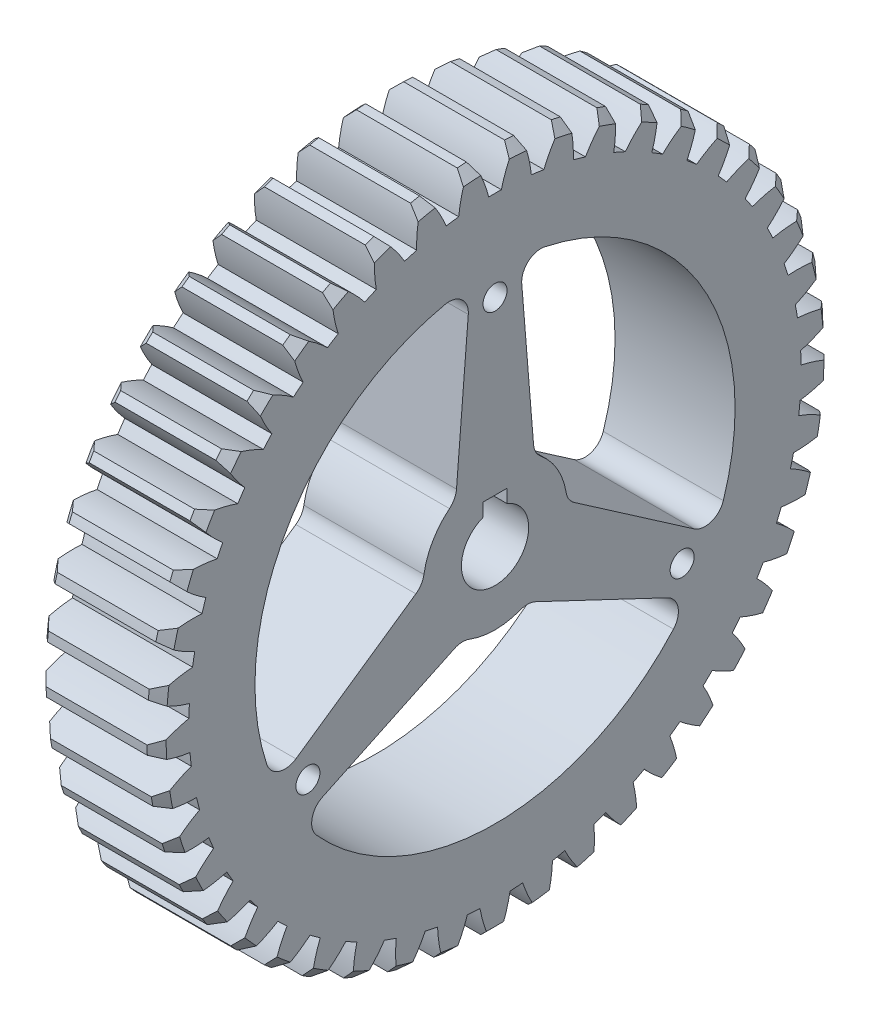
SolidWorks part; units mm, degrees
ref_plane "Plane1" through (0, 0, 0) normal (0, 0, 1) x (1, 0, 0)
ref_plane "Plane2" through (0, 0, 0) normal (0, 1, 0) x (1, 0, 0)
ref_plane "Plane3" through (0, 0, 0) normal (1, 0, 0) x (0, 0, -1)
sketch "HoldingSke" plane through (0, 0, 0) normal (0, 1, 0) x (1, 0, 0)
  line L0 (0, 0) -> (0.2357, -0.2357)
  line L1 (-15, 0) -> (100, 0) construction
  line L2 (0, 0) -> (-2.1039, 2.3779)
  line L3 (0, 0) -> (-11.863, 4.5341)
  line L4 (0, 0) -> (6.1066, 6.1066)
  line L5 (0, 0) -> (-46.8476, -17.4728)
  line L6 (0, 0) -> (-24.8689, -16.7791)
  line L7 (-2.1039, 2.3779) -> (8.6586, 51.2059)
  line L8 (-76.2, 54.61) -> (-73.9, 54.61)
  line L9 (-71.009, 38.7566) -> (-53.1078, 45.2721)
  line L10 (-76.2, 71.12) -> (104.1128, 71.12)
  line L11 (0, 0) -> (-30, 0)
  line L12 (-76.2, 101.6) -> (-76.093, 101.6)
  line L13 (24.9733, 27.94) -> (52.9518, 28.4284)
  line L14 (24.9733, 27.94) -> (24.9743, 27.94)
  line L15 (24.9733, 27.94) -> (100.4006, 29.5858)
  line L16 (-63.627, -3) -> (-12.827, -3)
  circle A0 centre (0, 0) radius 7
  circle A1 centre (0, 0) radius 37.5
  circle A2 centre (0, 0) radius 37.5
  circle A3 centre (0, 0) radius 7
  dimension "MHD" = 75
  dimension "Hub_dia" = 75
  dimension "Bore" = 14
  dimension "MBD" = 14
  dimension "Num_teeth" = 45
  dimension "Pitch" = 0.3333
  dimension "Overall_len" = 50
  dimension "Show_teeth" = 45
  dimension "Thickness" = 30
  dimension "OAL" = 50.0001
  dimension "T_dim" = 2.3
  dimension "Ap" = 20
  dimension "H" = 19.05
  dimension "Pitch_radius" = 180.3128
  dimension "Width" = 30
  dimension "Backlash" = 0.107
  dimension "Addendum_fac" = 1
  dimension "Dedendum_fac" = 1.25
  dimension "Clearance_fac" = 0.25
  dimension "Dedendum_add" = 0.001
  dimension "Module" = 3
sketch "BasProSke" plane through (0, 0, 0) normal (0, 1, 0) x (1, 0, 0)
  line L0 (-10, 0) -> (60, 0) construction
  line L1 (0, 0) -> (0, 70.5)
  line L2 (0, 0) -> (25, 0)
  line L3 (25, 0) -> (25, 70.5)
  line L4 (25, 70.5) -> (0, 70.5)
  dimension "Thickness" = 25
  dimension "Diameter" = 141
revolve "Base-Revolve" add sketch "BasProSke" angle 360 about L0
chamfer "倒角1" distance 2 angle 45 2 edges at (25, 0, 70.5) (0, 0, 70.5)
sketch "TooCutSke" plane through (0, 0, 0) normal (1, 0, 0) x (0, 0, -1)
  line L1 (0, 0) -> (0, 107) construction
  line L2 (0, 0) -> (-2.5429, 67.4521) construction
  line L3 (0, 0) -> (-9.4123, 134.6016) construction
  line L4 (-2.5429, 67.4521) -> (-4.7061, 67.3008) construction
  arc A0 (1.3167, 63.7354) -> (-1.3167, 63.7354) centre (0, 0) ccw
  arc A1 (3.9813, 70.4129) -> (-3.9813, 70.4129) centre (0, 0) ccw
  circle A2 centre (0, 0) radius 67.5 construction
  circle A3 centre (0, 0) radius 63.4293 construction
  arc A4 (-1.3167, 63.7354) -> (-3.9813, 70.4129) centre (-27.5029, 57.1564) ccw
  arc A5 (3.9813, 70.4129) -> (1.3167, 63.7354) centre (27.5029, 57.1564) ccw
  dimension "Root_dia" = 127.498
  dimension "Overcut_dia" = 141.0508
  dimension "Pitch_dia" = 135
  dimension "Base_dia" = 126.8585
  dimension "Flank_rad" = 27
  dimension "Half_ang" = 4
  dimension "Half_CT" = 2.1685
extrude "ToothCut" cut sketch "TooCutSke" along normal through all
fillet "Breaks" [suppressed] radius 0.06
fillet "RootFillets" [suppressed] radius 0.751
pattern_circular "TeethCuts" count 45 every 8 about axis through (-10, 0, 0) along (1, 0, 0) of "ToothCut", "RootFillets", "Breaks"
sketch "HubNeaOneSke" plane through (0, 0, 0) normal (-1, 0, 0) x (0, 0, 1)
  circle A0 centre (0, 0) radius 37.5
  dimension "Diameter" = 75
extrude "HubNearOne" [suppressed] add sketch "HubNeaOneSke" along normal blind 25.0001
sketch "HubNeaBotSke" plane through (0, 0, 0) normal (-1, 0, 0) x (0, 0, 1)
  circle A0 centre (0, 0) radius 37.5
  dimension "Diameter" = 75
extrude "HubNearBoth" [suppressed] add sketch "HubNeaBotSke" along normal blind 12.5
ref_plane "FarPln" through (25, 0, 0) normal (1, 0, 0) x (0, 0, -1)
sketch "HubFarSke" plane through (25, 0, 0) normal (1, 0, 0) x (0, 0, -1)
  circle A0 centre (0, 0) radius 37.5
  dimension "Diameter" = 75
extrude "HubFar" [suppressed] add sketch "HubFarSke" along normal blind 12.5
sketch "BorSke" plane through (0, 0, 0) normal (1, 0, 0) x (0, 0, -1)
  circle A0 centre (0, 0) radius 7
  dimension "Diameter" = 14
extrude "Bore" cut sketch "BorSke" along normal mid plane 100.0001
sketch "KeySke" plane through (0, 0, 0) normal (1, 0, 0) x (0, 0, -1)
  line L0 (-2.5, 0) -> (-2.5, 9.3)
  line L1 (-2.5, 9.3) -> (2.5, 9.3)
  line L2 (2.5, 9.3) -> (2.5, 0)
  line L3 (0, 0) -> (0, 34) construction
  line L4 (-2.5, 0) -> (2.5, 0)
  dimension "Offset" = 9.3
  dimension "Width" = 5
extrude "Keyway" cut sketch "KeySke" along normal mid plane 100.0001
pattern_circular "Keyway2" [suppressed] count 2 every 90 about axis through (-10, 0, 0) along (1, 0, 0)
sketch "草图1" plane through (0, 0, 0) normal (1, 0, 0) x (0, 0, -1)
  line L2 (0, 0) -> (-12.9904, 7.5) construction
  line L3 (-5.1571, 49.7333) -> (-8.1725, 12.5782)
  line L4 (0, 67.7355) -> (0, 0) construction
  line L5 (-45.6489, -20.4005) -> (-14.9793, 0.7885)
  line L6 (45.6489, -20.4005) -> (14.9793, 0.7885)
  line L7 (5.1571, 49.7333) -> (8.1725, 12.5782)
  line L8 (-40.4918, -29.3328) -> (-6.8068, -13.3667)
  line L9 (40.4918, -29.3328) -> (6.8068, -13.3667)
  arc A0 (-8.1725, 12.5782) -> (-14.9793, 0.7885) centre (0, 0) ccw
  arc A1 (-5.1571, 49.7333) -> (-45.6489, -20.4005) centre (0, 0) ccw
  circle A3 centre (-12.9904, 7.5) radius 7 construction
  circle A4 centre (-0.5157, 54.9733) radius 7 construction
  arc A5 (45.6489, -20.4005) -> (5.1571, 49.7333) centre (0, 0) ccw
  arc A6 (14.9793, 0.7885) -> (8.1725, 12.5782) centre (0, 0) ccw
  arc A7 (-40.4918, -29.3328) -> (40.4918, -29.3328) centre (0, 0) ccw
  arc A8 (-6.8068, -13.3667) -> (6.8068, -13.3667) centre (0, 0) ccw
  dimension "D2" = 14
  dimension "D3" = 100
  dimension "D4" = 3
  dimension "D5" = 30
  dimension "D6" = 14
  dimension "D1" = 60
extrude "切除-拉伸1" cut sketch "草图1" along normal through all
sketch "草图2" plane through (0, 0, 0) normal (1, 0, 0) x (0, 0, -1)
  circle A0 centre (0, 45) radius 2.5
  circle A4 centre (0, 0) radius 45 construction
  circle A5 centre (38.9711, -22.5) radius 2.5
  circle A6 centre (-38.9711, -22.5) radius 2.5
  dimension "D1" = 5
  dimension "D2" = 90
  dimension "D3" = 3
extrude "切除-拉伸2" cut sketch "草图2" along normal through all
sketch "草图3" plane through (0, 0, 0) normal (1, 0, 0) x (0, 0, -1)
  circle A0 centre (0, 30) radius 2
  circle A1 centre (25.9808, -15) radius 2
  circle A2 centre (-25.9808, -15) radius 2
  dimension "D1" = 4
  dimension "D3" = 3
extrude "切除-拉伸3" cut sketch "草图3" along normal blind 10
fillet "圆角1" radius 4 12 edges at (12.5, 12.5782, -8.1725) (12.5, 0.7885, -14.9793) (12.5, -13.3667, -6.8068) (12.5, -13.3667, 6.8068) (12.5, 0.7885, 14.9793) (12.5, 12.5782, 8.1725) (12.5, 49.7333, 5.1571) (12.5, 49.7333, -5.1571) (12.5, -20.4005, -45.6489) (12.5, -29.3328, -40.4918) (12.5, -29.3328, 40.4918) (12.5, -20.4005, 45.6489)
equation "' \"Module@HoldingSke\" = 6.35"
equation "' \"Num_teeth@HoldingSke\" = 12"
equation "' \"Ap@HoldingSke\" =  20"
equation "' \"Ap@HoldingSke\" = 20"
equation "' \"Width@HoldingSke\" = 0.5 * 25.4"
equation "' \"Hub_dia@HoldingSke\"= 1 * 25.4"
equation "' \"Hub_dia@HoldingSke\" = 1 * 25.4"
equation "' \"Overall_len@HoldingSke\" = 1.0 * 25.4"
equation "' \"Bore@HoldingSke\" = 0.75 * 25.4"
equation "' \"T_dim@HoldingSke\" = 0.1 * 25.4"
equation "' \"Width@KeySke\" = 0.25 * 25.4"
equation "' \"Show_teeth@HoldingSke\" = 13"
equation "' \"Backlash@HoldingSke\" = 0.009 * 25.4"
equation "' \"Addendum_fac@HoldingSke\" = 1.0"
equation "' \"Dedendum_fac@HoldingSke\" = 1.25"
equation "' \"Dedendum_add@HoldingSke\" = 0.00005 * 25.4"
equation "' \"Clearance_fac@HoldingSke\" = 0.25"
equation "\"Pitch@HoldingSke\" = 1 / \"Module@HoldingSke\""
equation "\"Overcut_dia@TooCutSke\" = (\"Num_teeth@HoldingSke\" + 2 * \"Addendum_fac@HoldingSke\") / \"Pitch@HoldingSke\" + 0.002 * 25.4"
equation "\"Pitch_dia@TooCutSke\" = \"Num_teeth@HoldingSke\" / \"Pitch@HoldingSke\""
equation "\"Base_dia@TooCutSke\" = \"Num_teeth@HoldingSke\" / \"Pitch@HoldingSke\" * cos((\"Ap@HoldingSke\"  * 3.14159265 / 180))"
equation "\"Root_dia@TooCutSke\" = (\"Num_teeth@HoldingSke\" + 2) / \"Pitch@HoldingSke\" - 2 * (\"Addendum_fac@HoldingSke\" + \"Dedendum_fac@HoldingSke\") / \"Pitch@HoldingSke\" - \"Dedendum_add@HoldingSke\" * 2"
equation "\"Half_ang@TooCutSke\" = 180 / \"Num_teeth@HoldingSke\""
equation "\"Half_CT@TooCutSke\" = \"Num_teeth@HoldingSke\" / \"Pitch@HoldingSke\" * sin((3.14159265 / 2 / \"Num_teeth@HoldingSke\")) / 2 - 7 * \"Backlash@HoldingSke\" / 4"
equation "\"Flank_rad@TooCutSke\" = \"Num_teeth@HoldingSke\" / \"Pitch@HoldingSke\" / 5"
equation "\"Radius@RootFillets\" = \"Clearance_fac@HoldingSke\" / \"Pitch@HoldingSke\" + \"Dedendum_add@HoldingSke\""
equation "\"Break_rad@Breaks\" = 0.02 / \"Pitch@HoldingSke\""
equation "\"Thickness@HoldingSke\" = \"Width@HoldingSke\""
equation "\"OAL@HoldingSke\" = \"Thickness@HoldingSke\""
equation "\"MHD@HoldingSke\" = (\"Num_teeth@HoldingSke\" + 2) / \"Pitch@HoldingSke\" - 2 * (\"Addendum_fac@HoldingSke\" + \"Dedendum_fac@HoldingSke\")  / \"Pitch@HoldingSke\" - \"Dedendum_add@HoldingSke\" * 2"
equation "\"MBD@HoldingSke\" = (\"Num_teeth@HoldingSke\" + 2) / \"Pitch@HoldingSke\" - 2 * (\"Addendum_fac@HoldingSke\" + \"Dedendum_fac@HoldingSke\")  / \"Pitch@HoldingSke\" - \"Dedendum_add@HoldingSke\" * 2 - 0.002 * 25.4"
equation "\"MHD@HoldingSke\" = ((sgn( \"MHD@HoldingSke\" - \"Hub_dia@HoldingSke\" )-1)*( \"MHD@HoldingSke\" - \"Hub_dia@HoldingSke\" ))/-2+ \"Hub_dia@HoldingSke\""
equation "\"MBD@HoldingSke\" = ((sgn( \"MBD@HoldingSke\" - \"Bore@HoldingSke\" )-1)*( \"MBD@HoldingSke\" - \"Bore@HoldingSke\" ))/-2+ \"Bore@HoldingSke\""
equation "\"OAL@HoldingSke\" = ((sgn( \"OAL@HoldingSke\" - \"Overall_len@HoldingSke\" )+1)*( \"OAL@HoldingSke\" - \"Overall_len@HoldingSke\" ))/2 + \"Overall_len@HoldingSke\" + 0.000002 * 25.4"
equation "\"Num_teeth@TeethCuts\" = int( \"Show_teeth@HoldingSke\" ) + 1"
equation "\"Num_teeth@TeethCuts\" = ((sgn( \"Num_teeth@TeethCuts\" - \"Num_teeth@HoldingSke\" )-1)*( \"Num_teeth@TeethCuts\" - \"Num_teeth@HoldingSke\" ))/-2+ \"Num_teeth@HoldingSke\""
equation "\"Num_teeth@TeethCuts\" = ((sgn( \"Num_teeth@TeethCuts\" - 2.0)+1)*( \"Num_teeth@TeethCuts\" - 2.0))/2 +2.0"
equation "\"Angle@TeethCuts\" = 360.0 / \"Num_teeth@HoldingSke\""
equation "\"Diameter@BasProSke\" = (\"Num_teeth@HoldingSke\" + 2 * \"Addendum_fac@HoldingSke\") / \"Pitch@HoldingSke\""
equation "' \"Fillet_rad@BasProSke\" =  \"Thickness@HoldingSke\" * 0.05"
equation "' \"Fillet_rad@BasProSke\" = \"Thickness@HoldingSke\" * 0.05"
equation "\"MHD@HoldingSke\" = ((sgn( \"MHD@HoldingSke\" - \"Root_dia@TooCutSke\" )-1)*( \"MHD@HoldingSke\" - \"Root_dia@TooCutSke\" ))/-2+ \"Root_dia@TooCutSke\""
equation "\"Diameter@HubNeaOneSke\" = \"MHD@HoldingSke\""
equation "\"Length@HubNearOne\" = \"OAL@HoldingSke\" - \"Thickness@BasProSke\""
equation "\"Diameter@HubNeaBotSke\" = \"MHD@HoldingSke\""
equation "\"Length@HubNearBoth\" = ( \"OAL@HoldingSke\" - \"Thickness@BasProSke\" ) / 2.0"
equation "\"Thickness@FarPln\" = \"Thickness@BasProSke\""
equation "\"Diameter@HubFarSke\" = \"MHD@HoldingSke\""
equation "\"Length@HubFar\" = ( \"OAL@HoldingSke\" - \"Thickness@BasProSke\" ) / 2.0"
equation "\"Diameter@BorSke\" = \"MBD@HoldingSke\""
equation "\"D1@Bore\" = \"OAL@HoldingSke\" * 2.0"
equation "\"D1@Keyway\" = \"OAL@HoldingSke\" * 2.0"
equation "\"Offset@KeySke\" = \"T_dim@HoldingSke\" + \"MBD@HoldingSke\" / 2.0"
